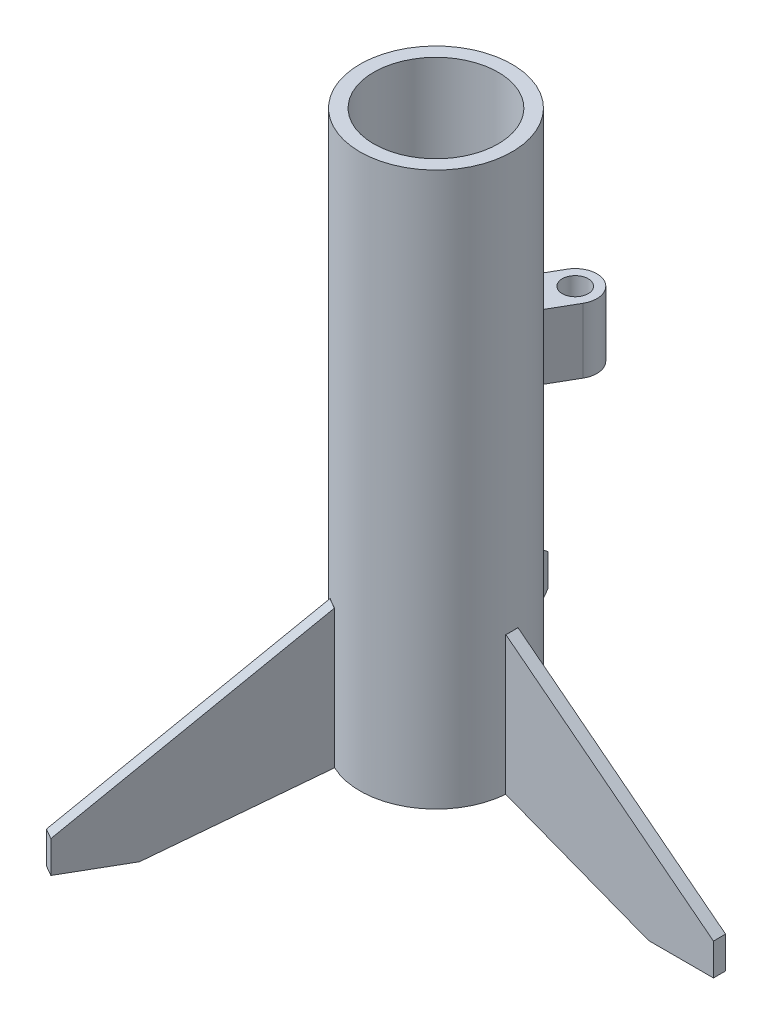
SolidWorks part; units mm, degrees
ref_plane "Front Plane" through (0, 0, 0) normal (0, 0, 1) x (1, 0, 0)
ref_plane "Top Plane" through (0, 0, 0) normal (0, 1, 0) x (1, 0, 0)
ref_plane "Right Plane" through (0, 0, 0) normal (1, 0, 0) x (0, 0, -1)
sketch "Sketch1" plane through (0, 0, 0) normal (0, 1, 0) x (1, 0, 0)
  circle A0 centre (0, 0) radius 9.1313
  circle A1 centre (0, 0) radius 11.1633
  dimension "D1" = 2.032
  dimension "D2" = 18.2626
extrude "Boss-Extrude1" add sketch "Sketch1" along normal blind 81.28
sketch "Sketch2" plane through (0, 0, 0) normal (0, 0, 1) x (1, 0, 0)
  line L0 (11.1633, 0) -> (9.1313, 0)
  line L1 (9.1313, 0) -> (9.1313, 20.32)
  line L2 (9.1313, 20.32) -> (11.1633, 20.32)
  line L3 (11.1633, 0) -> (11.1633, 81.28) construction
  line L4 (11.1633, 20.32) -> (41.6433, -3.408)
  line L5 (41.6433, -3.408) -> (41.6433, -8.1032)
  line L6 (32.1183, -8.1032) -> (11.1633, 0)
  line L7 (32.1183, -8.1032) -> (41.6433, -8.1032)
  line L8 (11.1633, 0) -> (11.1633, 81.28) construction
  dimension "D1" = 111.141
  dimension "D2" = 20.32
  dimension "D3" = 30.48
  dimension "D4" = 52.1
  dimension "D5" = 9.525
extrude "Boss-Extrude2" add sketch "Sketch2" along normal mid plane 1.778
pattern_circular "CirPattern1" count 3 over 360 about axis through (0, 0, 0) along (0, 1, 0) of "Boss-Extrude2"
ref_plane "Plane2" through (0, 63.5, 0) normal (0, 1, 0) x (1, 0, 0)
sketch "Sketch3" plane through (0, 63.5, 0) normal (0, 1, 0) x (1, 0, 0)
  circle A0 centre (0, 0) radius 6.35
  circle A1 centre (0, 0) radius 9.1313 construction
  circle A2 centre (0, 0) radius 9.1313
  dimension "D1" = 12.7
extrude "Boss-Extrude3" add sketch "Sketch3" along normal blind 3.175
ref_plane "Plane3" through (5.5817, 0, -9.6677) normal (0.5, 0, -0.866) x (0, -1, 0)
sketch "Sketch5" plane through (5.5817, 0, -9.6677) normal (0.5, 0, -0.866) x (0, -1, 0)
  line L0 (-81.28, 11.1633) -> (-81.28, -11.1633) construction
  line L1 (-55.88, -3.175) -> (-46.355, -3.175)
  line L2 (-55.88, -3.175) -> (-55.88, 3.175)
  line L3 (-55.88, 3.175) -> (-46.355, 3.175)
  line L4 (-46.355, -3.175) -> (-46.355, 3.175)
  line L5 (-55.88, -3.175) -> (-46.355, 3.175) construction
  line L6 (-55.88, 3.175) -> (-46.355, -3.175) construction
  point P0 (-51.1175, 0)
  point P7 (-56.1975, 0)
  point P8 (0, 0)
  dimension "D1" = 25.4
  dimension "D2" = 9.525
  dimension "D3" = 6.35
extrude "Boss-Extrude4" add sketch "Sketch5" along normal blind 3.81 and the other way up to surface
sketch "Sketch6" plane through (0, 55.88, 0) normal (0, 1, 0) x (1, 0, 0)
  line L0 (4.737, 14.5548) -> (10.2363, 11.3798) construction
  line L1 (4.737, 14.5548) -> (2.6015, 10.8559) construction
  line L2 (4.737, 14.5548) -> (10.2363, 11.3798)
  arc A0 (10.2363, 11.3798) -> (4.737, 14.5548) centre (7.4867, 12.9673) ccw
extrude "Boss-Extrude5" add sketch "Sketch6" against normal up to surface (9.525 mm away) up to face at (6.4765, 46.355, -11.2177)
sketch "Sketch7" plane through (0, 55.88, 0) normal (0, 1, 0) x (1, 0, 0)
  circle A0 centre (7.4867, 12.9673) radius 1.905
  dimension "D1" = 3.81
extrude "Cut-Extrude1" cut sketch "Sketch7" against normal up to surface (9.525 mm away) up to face at (6.8734, 46.355, -11.9051)
